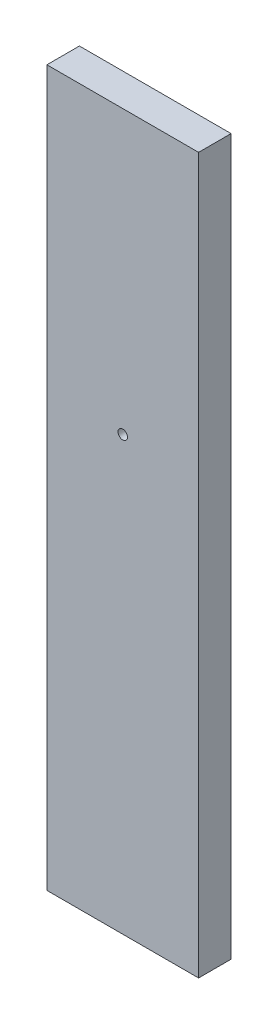
SolidWorks part; units mm, degrees
ref_plane "Front Plane" through (0, 0, 0) normal (0, 0, 1) x (1, 0, 0)
ref_plane "Top Plane" through (0, 0, 0) normal (0, 1, 0) x (1, 0, 0)
ref_plane "Right Plane" through (0, 0, 0) normal (1, 0, 0) x (0, 0, -1)
sketch "Sketch1" plane through (0, 0, 0) normal (0, 1, 0) x (1, 0, 0)
  line L1 (0, 0) -> (88.9, 0)
  line L2 (0, 0) -> (0, 19.05)
  line L3 (0, 19.05) -> (88.9, 19.05)
  line L4 (88.9, 0) -> (88.9, 19.05)
  dimension "D1" = 19.05
  dimension "D2" = 88.9
extrude "Boss-Extrude1" add sketch "Sketch1" along normal blind 419.1
sketch "Sketch2" plane through (0, 0, 0) normal (0, 0, 1) x (1, 0, 0)
  line L0 (44.45, 419.1) -> (44.45, 253.6518) construction
  line L1 (0, 419.1) -> (88.9, 419.1) construction
  circle A0 centre (44.45, 253.6518) radius 2.7781
  dimension "D1" = 5.5562
  dimension "D2" = 165.4482
extrude "Cut-Extrude1" cut sketch "Sketch2" against normal through all
